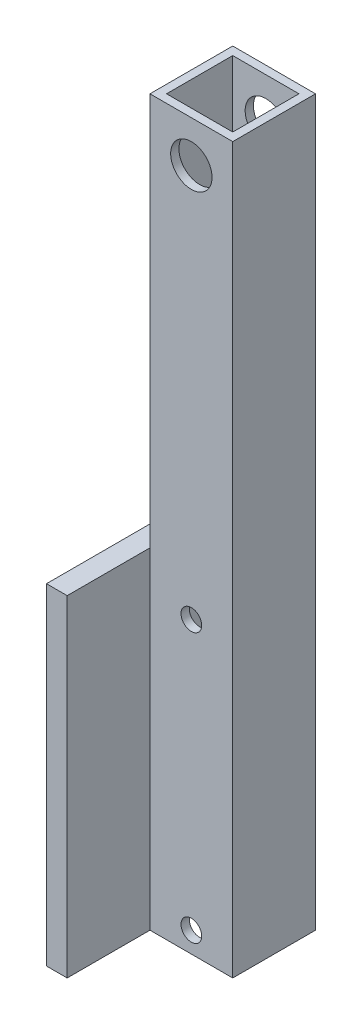
SolidWorks part; units mm, degrees
material "6061 Alloy"
ref_plane "Front Plane" through (0, 0, 0) normal (0, 0, 1) x (1, 0, 0)
ref_plane "Top Plane" through (0, 0, 0) normal (0, 1, 0) x (1, 0, 0)
ref_plane "Right Plane" through (0, 0, 0) normal (1, 0, 0) x (0, 0, -1)
sketch "Sketch1" plane through (0, 0, 0) normal (0, 1, 0) x (1, 0, 0)
  line L0 (-10.16, 10.16) -> (10.16, 10.16)
  line L1 (-12.7, 12.7) -> (12.7, 12.7)
  line L2 (-12.7, 12.7) -> (-12.7, -12.7)
  line L3 (-12.7, -12.7) -> (12.7, -12.7)
  line L4 (12.7, 12.7) -> (12.7, -12.7)
  line L5 (-12.7, 12.7) -> (12.7, -12.7) construction
  line L6 (-12.7, -12.7) -> (12.7, 12.7) construction
  line L7 (10.16, 10.16) -> (10.16, -10.16)
  line L8 (-10.16, -10.16) -> (10.16, -10.16)
  line L9 (-10.16, 10.16) -> (-10.16, -10.16)
  point P0 (0, 0)
  dimension "D1" = 25.4
  dimension "D2" = 25.4
  dimension "D3" = 2.54
extrude "Boss-Extrude1" add sketch "Sketch1" along normal blind 222.25
sketch "Sketch2" plane through (0, 0, 12.7) normal (0, 0, 1) x (1, 0, 0)
  line L0 (0, 222.25) -> (0, 0) construction
  line L1 (-12.7, 222.25) -> (12.7, 222.25) construction
  line L2 (-12.7, 0) -> (12.7, 0) construction
  circle A0 centre (0, 209.55) radius 6.35
  circle A1 centre (0, 6.35) radius 3.175
  circle A2 centre (0, 88.9) radius 3.175
  dimension "D2" = 12.7
  dimension "D4" = 6.35
  dimension "D1" = 12.7
  dimension "D3" = 6.35
  dimension "D5" = 82.55
extrude "Cut-Extrude1" cut sketch "Sketch2" against normal blind 222.25
sketch "Sketch4" plane through (-12.7, 0, 0) normal (-1, 0, 0) x (0, 0, 1)
  line L0 (-38.1, 101.6) -> (38.1, 101.6)
  line L5 (-38.1, 101.6) -> (-38.1, 0)
  line L6 (38.1, 0) -> (38.1, 101.6)
  line L7 (-38.1, 0) -> (38.1, 0)
  line L8 (-12.7, 0) -> (12.7, 0) construction
  point P2 (0, 0)
  dimension "D1" = 76.2
  dimension "D2" = 101.6
extrude "Boss-Extrude3" add sketch "Sketch4" along normal blind 6.35
sketch "Sketch5" plane through (12.7, 0, 0) normal (1, 0, 0) x (0, 0, -1)
  line L0 (-12.7, 111.125) -> (12.7, 111.125) construction
  line L1 (-12.7, 222.25) -> (-12.7, 0) construction
  line L2 (12.7, 222.25) -> (12.7, 0) construction
sketch "Sketch6" plane through (0, 0, 12.7) normal (0, 0, 1) x (1, 0, 0)
  line L0 (0, 88.9) -> (63.2036, 208.6339) construction
  point P3 (63.2036, 208.6339)
